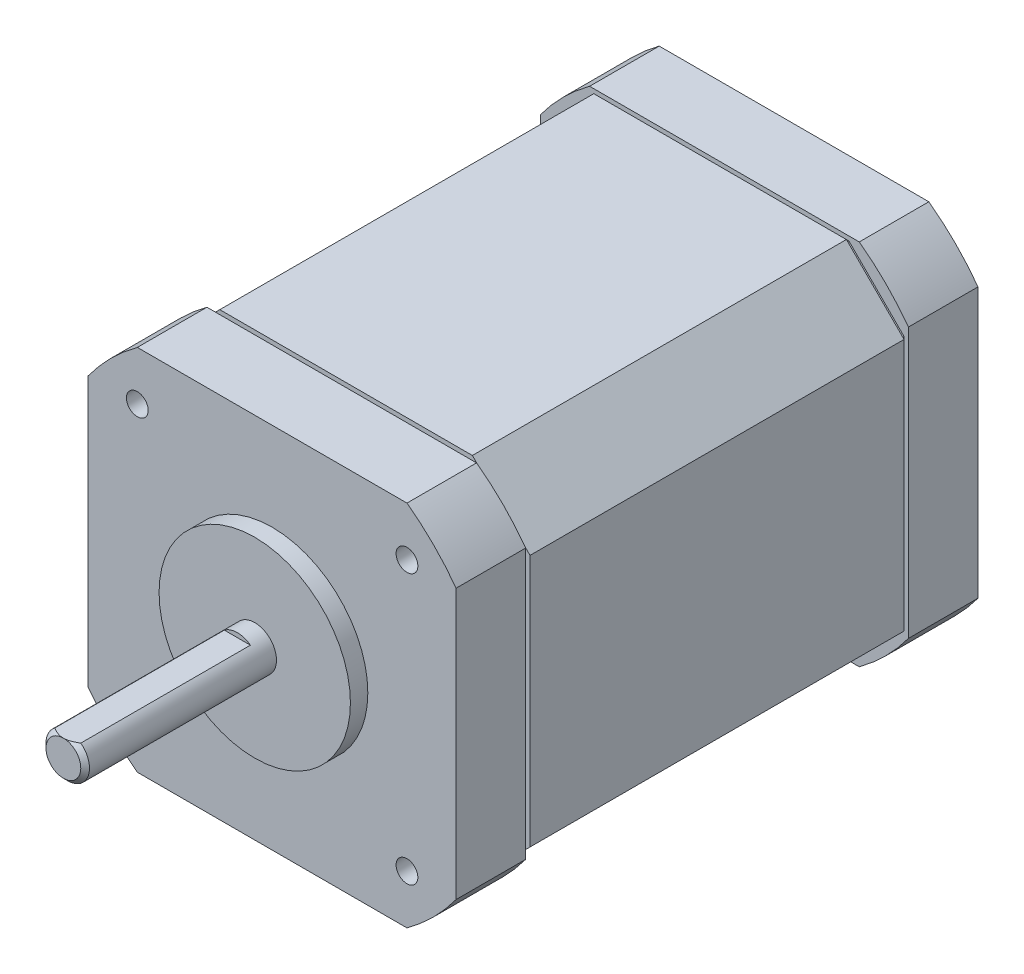
SolidWorks part; units mm, degrees
material "Alloy Steel"
ref_plane "Front Plane" through (0, 0, 0) normal (0, 0, 1) x (1, 0, 0)
ref_plane "Top Plane" through (0, 0, 0) normal (0, 1, 0) x (1, 0, 0)
ref_plane "Right Plane" through (0, 0, 0) normal (1, 0, 0) x (0, 0, -1)
sketch "Sketch1" plane through (0, 0, 0) normal (0, 0, 1) x (1, 0, 0)
  line L0 (-1.5, 2) -> (1.5, 2) construction
  circle A0 centre (0, 0) radius 2.5
  dimension "D1" = 5
  dimension "D2" = 2
extrude "Boss-Extrude1" add sketch "Sketch1" against normal blind 22
sketch "Sketch2" plane through (0, 0, -22) normal (0, 0, -1) x (-1, 0, 0)
  circle A0 centre (0, 0) radius 11
  dimension "D1" = 22
extrude "Boss-Extrude2" add sketch "Sketch2" along normal blind 2
sketch "Sketch3" plane through (0, 0, -24) normal (0, 0, -1) x (-1, 0, 0)
  line L1 (15.5, -21.15) -> (-15.5, -21.15)
  line L2 (21.15, -15.5) -> (21.15, 15.5)
  line L3 (15.5, 21.15) -> (-15.5, 21.15)
  line L4 (-21.15, -15.5) -> (-21.15, 15.5)
  line L5 (21.15, -21.15) -> (-21.15, 21.15) construction
  line L6 (21.15, 21.15) -> (-21.15, -21.15) construction
  arc A0 (-21.15, -15.5) -> (-15.5, -21.15) centre (0, 0) ccw
  arc A1 (-15.5, 21.15) -> (-21.15, 15.5) centre (0, 0) ccw
  arc A2 (21.15, 15.5) -> (15.5, 21.15) centre (0, 0) ccw
  arc A3 (15.5, -21.15) -> (21.15, -15.5) centre (0, 0) ccw
  dimension "D1" = 42.3
  dimension "D2" = 31
extrude "Boss-Extrude3" add sketch "Sketch3" along normal blind 8
sketch "Sketch6" plane through (0, 0, -32) normal (0, 0, -1) x (-1, 0, 0)
  line L0 (-20.65, -14.3116) -> (-14.3116, -20.65)
  line L1 (-14.3116, -20.65) -> (14.3116, -20.65)
  line L2 (14.3116, -20.65) -> (20.65, -14.3116)
  line L3 (20.65, -14.3116) -> (20.65, 14.3116)
  line L4 (20.65, 14.3116) -> (14.3116, 20.65)
  line L5 (14.3116, 20.65) -> (-14.3116, 20.65)
  line L6 (-14.3116, 20.65) -> (-20.65, 14.3116)
  line L7 (-20.65, 14.3116) -> (-20.65, -14.3116)
extrude "Boss-Extrude6" add sketch "Sketch6" along normal blind 0.5
sketch "Sketch4" plane through (0, 0, -32.5) normal (0, 0, -1) x (-1, 0, 0)
  line L0 (-21.15, 14.5187) -> (-14.5187, 21.15)
  line L1 (-21.15, 15.5) -> (-21.15, -15.5) construction
  line L2 (15.5, 21.15) -> (-15.5, 21.15) construction
  line L3 (-14.5187, 21.15) -> (14.5187, 21.15)
  line L4 (14.5187, 21.15) -> (21.15, 14.5187)
  line L5 (21.15, -15.5) -> (21.15, 15.5) construction
  line L6 (21.15, 14.5187) -> (21.15, -14.5187)
  line L7 (21.15, -14.5187) -> (14.5187, -21.15)
  line L8 (-15.5, -21.15) -> (15.5, -21.15) construction
  line L9 (14.5187, -21.15) -> (-14.5187, -21.15)
  line L10 (-14.5187, -21.15) -> (-21.15, -14.5187)
  line L11 (-21.15, -14.5187) -> (-21.15, 14.5187)
  line L12 (-18.5415, -18.5415) -> (-17.8344, -17.8344) construction
  arc A0 (-21.15, -15.5) -> (-15.5, -21.15) centre (0, 0) ccw construction
  dimension "D1" = 1
extrude "Boss-Extrude4" add sketch "Sketch4" along normal blind 43
sketch "Sketch7" plane through (0, 0, -75.5) normal (0, 0, -1) x (-1, 0, 0)
  line L8 (-20.65, -14.3116) -> (-14.3116, -20.65)
  line L9 (-14.3116, -20.65) -> (14.3116, -20.65)
  line L10 (14.3116, -20.65) -> (20.65, -14.3116)
  line L11 (20.65, -14.3116) -> (20.65, 14.3116)
  line L12 (20.65, 14.3116) -> (14.3116, 20.65)
  line L13 (14.3116, 20.65) -> (-14.3116, 20.65)
  line L14 (-14.3116, 20.65) -> (-20.65, 14.3116)
  line L15 (-20.65, 14.3116) -> (-20.65, -14.3116)
  line L16 (-20.65, -14.3116) -> (-14.3116, -20.65)
  line L17 (-14.3116, -20.65) -> (14.3116, -20.65)
  line L18 (14.3116, -20.65) -> (20.65, -14.3116)
  line L19 (20.65, -14.3116) -> (20.65, 14.3116)
  line L20 (20.65, 14.3116) -> (14.3116, 20.65)
  line L21 (14.3116, 20.65) -> (-14.3116, 20.65)
  line L22 (-14.3116, 20.65) -> (-20.65, 14.3116)
  line L23 (-20.65, 14.3116) -> (-20.65, -14.3116)
  dimension "D1" = 0
extrude "Boss-Extrude7" add sketch "Sketch7" along normal blind 0.5
sketch "Sketch5" plane through (0, 0, -76) normal (0, 0, -1) x (-1, 0, 0)
  line L4 (-15.5, -21.15) -> (15.5, -21.15)
  line L5 (-21.15, 15.5) -> (-21.15, -15.5)
  line L6 (15.5, 21.15) -> (-15.5, 21.15)
  line L7 (21.15, -15.5) -> (21.15, 15.5)
  line L8 (-15.5, -21.15) -> (15.5, -21.15)
  line L9 (-21.15, 15.5) -> (-21.15, -15.5)
  line L10 (15.5, 21.15) -> (-15.5, 21.15)
  line L11 (21.15, -15.5) -> (21.15, 15.5)
  arc A4 (-21.15, -15.5) -> (-15.5, -21.15) centre (0, 0) ccw
  arc A5 (-15.5, 21.15) -> (-21.15, 15.5) centre (0, 0) ccw
  arc A6 (21.15, 15.5) -> (15.5, 21.15) centre (0, 0) ccw
  arc A7 (15.5, -21.15) -> (21.15, -15.5) centre (0, 0) ccw
  arc A8 (-21.15, -15.5) -> (-15.5, -21.15) centre (0, 0) ccw
  arc A9 (-15.5, 21.15) -> (-21.15, 15.5) centre (0, 0) ccw
  arc A10 (21.15, 15.5) -> (15.5, 21.15) centre (0, 0) ccw
  arc A11 (15.5, -21.15) -> (21.15, -15.5) centre (0, 0) ccw
  dimension "D1" = 0
extrude "Boss-Extrude5" add sketch "Sketch5" along normal blind 8
chamfer "Chamfer1" distance 0.5 angle 45 1 edges at (2.5, 0, 0)
sketch "Sketch8" plane through (0, 0, 0) normal (0, 0, 1) x (1, 0, 0)
  line L0 (-1.5, 2) -> (1.5, 2) construction
  line L1 (-2.9352, 3.3435) -> (3.532, 3.3435)
  line L2 (-2.9352, 3.3435) -> (-2.9352, 2)
  line L3 (-2.9352, 2) -> (3.532, 2)
  line L4 (3.532, 3.3435) -> (3.532, 2)
extrude "Cut-Extrude1" cut sketch "Sketch8" against normal blind 20
sketch "Sketch9" plane through (0, 0, -24) normal (0, 0, 1) x (1, 0, 0)
  line L1 (15.5, -15.5) -> (-15.5, -15.5) construction
  line L2 (15.5, -15.5) -> (15.5, 15.5) construction
  line L3 (15.5, 15.5) -> (-15.5, 15.5) construction
  line L4 (-15.5, -15.5) -> (-15.5, 15.5) construction
  line L5 (15.5, -15.5) -> (-15.5, 15.5) construction
  line L6 (15.5, 15.5) -> (-15.5, -15.5) construction
  circle A0 centre (-15.5, 15.5) radius 1.25
  circle A1 centre (15.5, 15.5) radius 1.25
  circle A2 centre (15.5, -15.5) radius 1.25
  circle A3 centre (-15.5, -15.5) radius 1.25
  point P0 (0, 0)
  dimension "D2" = 2.5
  dimension "D1" = 31
extrude "Cut-Extrude2" cut sketch "Sketch9" against normal blind 10
